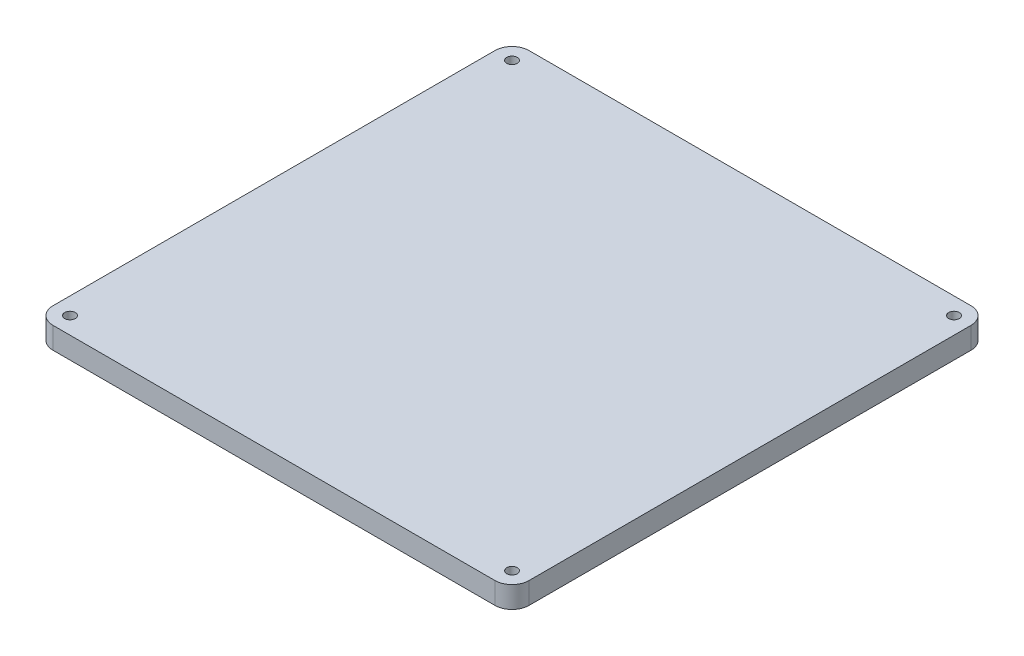
SolidWorks part; units mm, degrees
ref_plane "Front Plane" through (0, 0, 0) normal (0, 0, 1) x (1, 0, 0)
ref_plane "Top Plane" through (0, 0, 0) normal (0, 1, 0) x (1, 0, 0)
ref_plane "Right Plane" through (0, 0, 0) normal (1, 0, 0) x (0, 0, -1)
sketch "Sketch1" plane through (0, 0, 0) normal (0, 1, 0) x (1, 0, 0)
  line L1 (-50, -50) -> (50, -50) construction
  line L2 (-50, -50) -> (-50, 50) construction
  line L3 (-50, 50) -> (50, 50) construction
  line L4 (50, -50) -> (50, 50) construction
  line L5 (-50, -50) -> (50, 50) construction
  line L6 (-50, 50) -> (50, -50) construction
  line L7 (70, -70) -> (-70, -70)
  line L8 (70, -70) -> (70, 70)
  line L9 (70, 70) -> (-70, 70)
  line L10 (-70, -70) -> (-70, 70)
  line L11 (70, -70) -> (-70, 70) construction
  line L12 (70, 70) -> (-70, -70) construction
  point P0 (0, 0)
  point P6 (0, 0)
  dimension "D1" = 100
  dimension "D2" = 20
extrude "Boss-Extrude1" add sketch "Sketch1" along normal blind 6.35
fillet "Fillet1" radius 5 4 edges at (-70, 3.175, -70) (70, 3.175, -70) (70, 3.175, 70) (-70, 3.175, 70)
sketch "Sketch2" plane through (0, 6.35, 0) normal (0, 1, 0) x (1, 0, 0)
  circle A0 centre (-65, -65) radius 1.55
  circle A1 centre (65, -65) radius 1.55
  circle A2 centre (65, 65) radius 1.55
  circle A3 centre (-65, 65) radius 1.55
  dimension "D1" = 3.1
extrude "Cut-Extrude1" cut sketch "Sketch2" against normal through all
